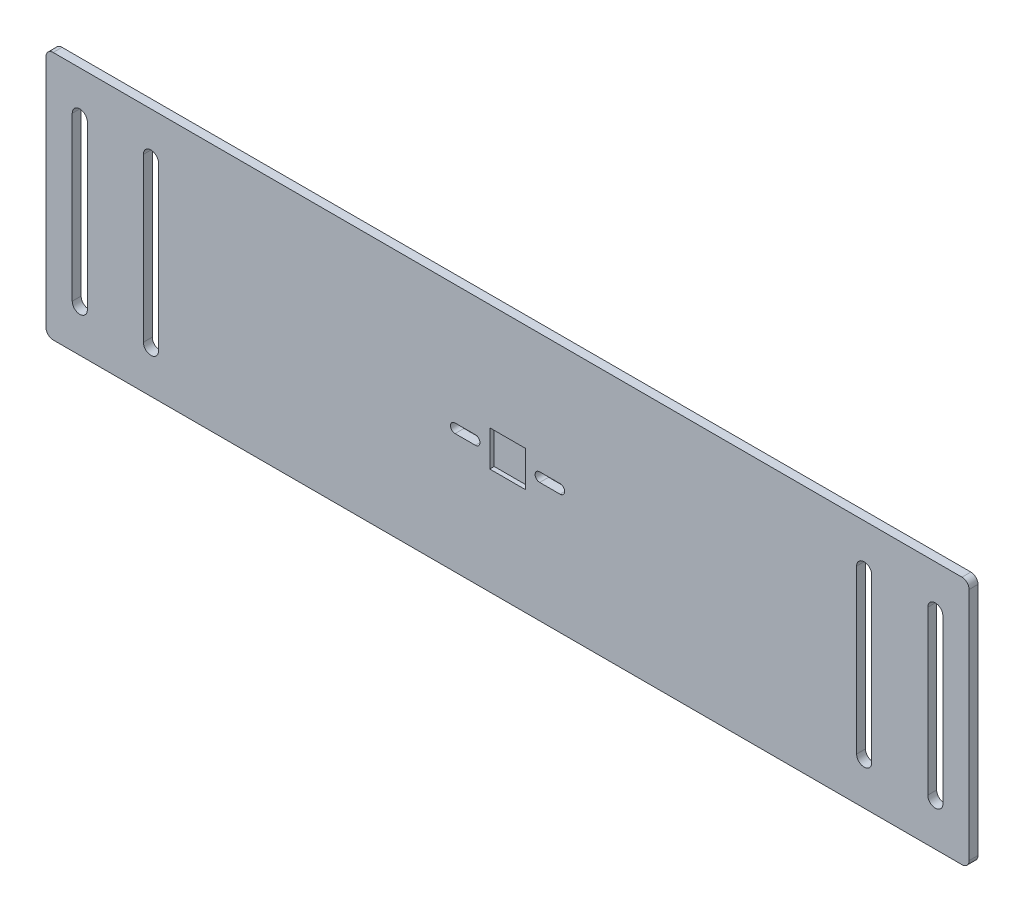
SolidWorks part; units mm, degrees
ref_plane "Front Plane" through (0, 0, 0) normal (0, 0, 1) x (1, 0, 0)
ref_plane "Top Plane" through (0, 0, 0) normal (0, 1, 0) x (1, 0, 0)
ref_plane "Right Plane" through (0, 0, 0) normal (1, 0, 0) x (0, 0, -1)
sketch "Sketch2" plane through (0, 0, -537.7708) normal (0, 0, 1) x (1, 0, 0)
  line L0 (-0.1188, 700) -> (-0.1188, 560) construction
  line L3 (-440.1188, 700) -> (-440.1188, 560) construction
  line L6 (-480.1188, 700) -> (-479.9788, 560) construction
  line L7 (38.8812, 700) -> (38.8812, 560) construction
  line L9 (-480.1188, 700) -> (38.8812, 700)
  line L10 (-480.1188, 700) -> (-480.1188, 560)
  line L11 (-480.1188, 560) -> (38.8812, 560)
  line L12 (38.8812, 700) -> (38.8812, 560)
  line L18 (15.6312, 700) -> (15.6312, 560) construction
  line L19 (24.1312, 700) -> (24.1312, 560) construction
  line L21 (-20.1188, 700) -> (-20.1188, 560) construction
  line L28 (-220.6188, 700) -> (-220.6188, 560) construction
  line L29 (-24.3688, 700) -> (-24.3688, 560) construction
  line L30 (-15.8688, 700) -> (-15.8688, 560) construction
  line L31 (24.1312, 700) -> (15.6312, 700)
  line L32 (19.8812, 700) -> (19.8812, 560) construction
  line L33 (19.8812, 584.25) -> (19.8812, 675.75) construction
  line L34 (15.6312, 584.25) -> (15.6312, 675.75)
  line L35 (24.1312, 584.25) -> (24.1312, 675.75)
  line L37 (19.8812, 580) -> (19.8812, 560) construction
  line L38 (-20.1188, 584.25) -> (-20.1188, 675.75) construction
  line L39 (-15.8688, 584.25) -> (-15.8688, 675.75)
  line L40 (-24.3688, 584.25) -> (-24.3688, 675.75)
  line L41 (-421.1188, 584.25) -> (-421.1188, 675.75) construction
  line L42 (-425.3688, 584.25) -> (-425.3688, 675.75)
  line L43 (-416.8688, 584.25) -> (-416.8688, 675.75)
  line L44 (-461.1188, 584.25) -> (-461.1188, 675.75) construction
  line L45 (-456.8688, 584.25) -> (-456.8688, 675.75)
  line L46 (-465.3688, 584.25) -> (-465.3688, 675.75)
  arc A4 (15.6312, 584.25) -> (24.1312, 584.25) centre (19.8812, 584.25) ccw
  arc A5 (24.1312, 675.75) -> (15.6312, 675.75) centre (19.8812, 675.75) ccw
  arc A6 (-15.8688, 584.25) -> (-24.3688, 584.25) centre (-20.1188, 584.25) cw
  arc A7 (-24.3688, 675.75) -> (-15.8688, 675.75) centre (-20.1188, 675.75) cw
  arc A8 (-425.3688, 584.25) -> (-416.8688, 584.25) centre (-421.1188, 584.25) ccw
  arc A9 (-416.8688, 675.75) -> (-425.3688, 675.75) centre (-421.1188, 675.75) ccw
  arc A10 (-456.8688, 584.25) -> (-465.3688, 584.25) centre (-461.1188, 584.25) cw
  arc A11 (-465.3688, 675.75) -> (-456.8688, 675.75) centre (-461.1188, 675.75) cw
  point P34 (19.8812, 700)
  point P39 (-20.1188, 675.25)
  point P40 (-20.1188, 574.75)
  point P41 (-20.1188, 574.75)
  point P42 (-20.1188, 560)
  point P43 (19.8812, 630)
  point P44 (-20.1188, 560)
  point P49 (19.8812, 680)
  point P50 (19.8812, 580)
  point P57 (-20.1188, 630)
  point P64 (-421.1188, 630)
  point P71 (-461.1188, 630)
  line M5 (-14.8688, 700) -> (-14.8688, -300)
  line M7 (14.6312, -300) -> (14.6312, 700)
  line M8 (14.6312, 700) -> (-14.8688, 700)
  dimension "D3" = 20
  dimension "D1" = 8.5
  dimension "D2" = 100
  dimension "D4" = 8.5
  dimension "D5" = 140
  dimension "D6" = 20
extrude "Boss-Extrude3" add sketch "Sketch2" along normal blind 5 contours L10 L11 L9 A9 L43 A8 L42 L40 A7 L39 A6 L46 A11 L45 A10 M5 | L11 M5 M7 M8 | L12 L9 L11 A5 L35 A4 L34 M7
fillet "Fillet1" radius 4 4 edges at (38.8812, 700, -535.2708) (-480.1188, 560, -535.2708) (-480.1188, 700, -535.2708) (38.8812, 560, -535.2708)
sketch "Sketch5" plane through (0, 0, -532.7708) normal (0, 0, 1) x (1, 0, 0)
  line L1 (-230.6188, 619.9) -> (-210.5188, 619.9)
  line L2 (-230.6188, 619.9) -> (-230.6188, 640)
  line L3 (-230.6188, 640) -> (-210.5188, 640)
  line L4 (-210.5188, 619.9) -> (-210.5188, 640)
  dimension "D1" = 20.1
  dimension "D2" = 20.1
extrude "Cut-Extrude1" cut sketch "Sketch5" against normal blind 2.5
sketch "Sketch6" plane through (0, 0, -532.7708) normal (0, 0, 1) x (1, 0, 0)
  line L0 (-191.0988, 632.575) -> (-202.5522, 632.575) construction
  line L1 (-202.5522, 627.425) -> (-191.0988, 627.425) construction
  line L2 (-250.1388, 627.425) -> (-238.6855, 627.425) construction
  line L3 (-238.6855, 632.575) -> (-250.1388, 632.575) construction
  line L4 (-191.0988, 632.575) -> (-202.5522, 632.575)
  line L5 (-202.5522, 627.425) -> (-191.0988, 627.425)
  line L6 (-250.1388, 627.425) -> (-238.6855, 627.425)
  line L7 (-238.6855, 632.575) -> (-250.1388, 632.575)
  arc A0 (-191.0988, 627.425) -> (-191.0988, 632.575) centre (-191.0988, 630) ccw construction
  arc A1 (-202.5522, 632.575) -> (-202.5522, 627.425) centre (-202.5522, 630) ccw construction
  arc A2 (-238.6855, 627.425) -> (-238.6855, 632.575) centre (-238.6855, 630) ccw construction
  arc A3 (-250.1388, 632.575) -> (-250.1388, 627.425) centre (-250.1388, 630) ccw construction
  arc A4 (-191.0988, 627.425) -> (-191.0988, 632.575) centre (-191.0988, 630) ccw
  arc A5 (-202.5522, 632.575) -> (-202.5522, 627.425) centre (-202.5522, 630) ccw
  arc A6 (-238.6855, 627.425) -> (-238.6855, 632.575) centre (-238.6855, 630) ccw
  arc A7 (-250.1388, 632.575) -> (-250.1388, 627.425) centre (-250.1388, 630) ccw
extrude "Cut-Extrude2" cut sketch "Sketch6" against normal blind 10
equation "\"2.5.00mm\"=10"
